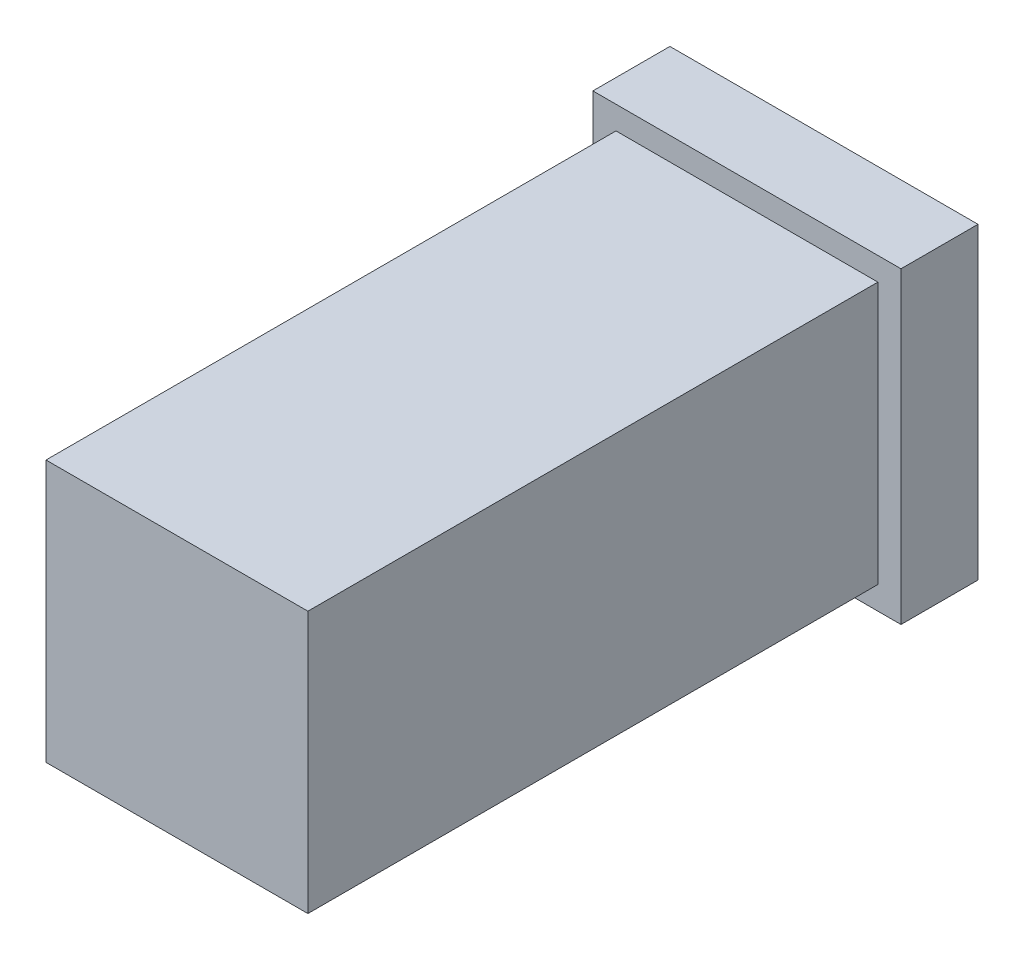
SolidWorks part; units mm, degrees
ref_plane "正面" through (0, 0, 0) normal (0, 0, 1) x (1, 0, 0)
ref_plane "平面" through (0, 0, 0) normal (0, 1, 0) x (1, 0, 0)
ref_plane "右側面" through (0, 0, 0) normal (1, 0, 0) x (0, 0, -1)
sketch "ｽｹｯﾁ1" plane through (0, 0, 0) normal (0, 0, 1) x (1, 0, 0)
  line L1 (-10, 10) -> (10, 10)
  line L2 (-10, 10) -> (-10, -10)
  line L3 (-10, -10) -> (10, -10)
  line L4 (10, 10) -> (10, -10)
  line L5 (-10, 10) -> (10, -10) construction
  line L6 (-10, -10) -> (10, 10) construction
  point P0 (0, 0)
  dimension "D1" = 20
  dimension "D2" = 20
extrude "ﾎﾞｽ - 押し出し1" add sketch "ｽｹｯﾁ1" along normal blind 5
sketch "ｽｹｯﾁ2" plane through (0, 0, 5) normal (0, 0, 1) x (1, 0, 0)
  line L1 (-8.5, 8.5) -> (8.5, 8.5)
  line L2 (-8.5, 8.5) -> (-8.5, -8.5)
  line L3 (-8.5, -8.5) -> (8.5, -8.5)
  line L4 (8.5, 8.5) -> (8.5, -8.5)
  line L5 (-8.5, 8.5) -> (8.5, -8.5) construction
  line L6 (-8.5, -8.5) -> (8.5, 8.5) construction
  point P0 (0, 0)
  dimension "D1" = 17
  dimension "D2" = 17
extrude "ﾎﾞｽ - 押し出し2" add sketch "ｽｹｯﾁ2" along normal blind 37
sketch "ｽｹｯﾁ3" plane through (0, 0, 0) normal (0, 0, -1) x (-1, 0, 0)
  circle A0 centre (0, 0) radius 4
  dimension "D1" = 8
extrude "ｶｯﾄ - 押し出し1" cut sketch "ｽｹｯﾁ3" against normal blind 10
